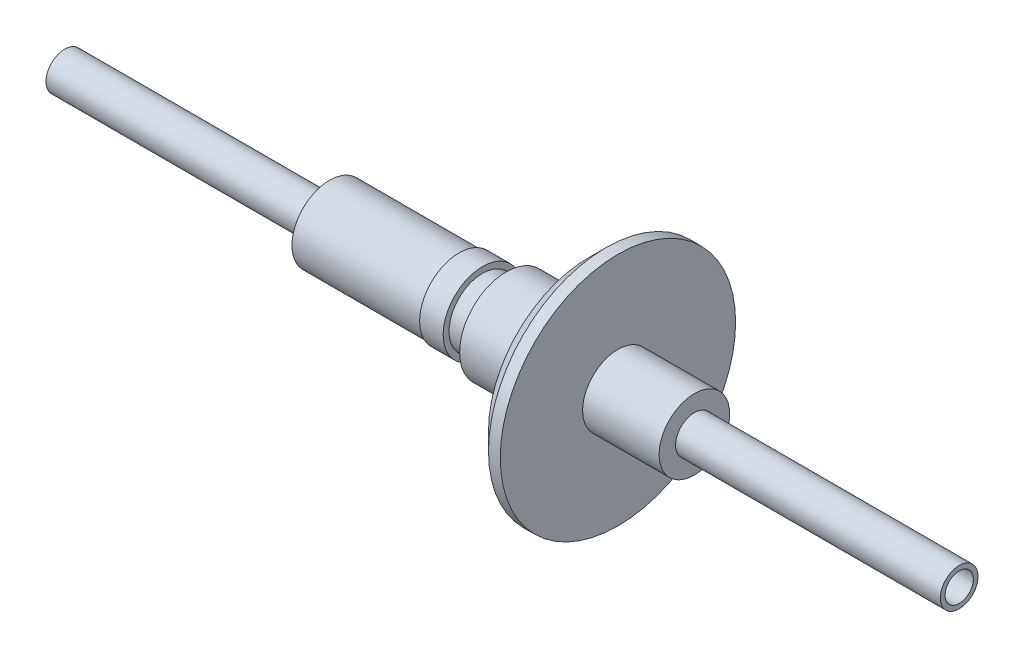
SolidWorks part; units mm, degrees
ref_plane "Front Plane" through (0, 0, 0) normal (0, 0, 1) x (1, 0, 0)
ref_plane "Top Plane" through (0, 0, 0) normal (0, 1, 0) x (1, 0, 0)
ref_plane "Right Plane" through (0, 0, 0) normal (1, 0, 0) x (0, 0, -1)
sketch "Axial profile (mm)" plane through (0, 0, 0) normal (0, 0, 1) x (1, 0, 0)
  line L0 (-110, 0) -> (75, 0) construction
  line L1 (-94, 2.4) -> (58, 2.4)
  line L2 (58, 2.4) -> (58, 3.2)
  line L3 (58, 3.2) -> (13, 3.2)
  line L4 (13, 3.2) -> (13, 6)
  line L5 (13, 6) -> (0, 6)
  line L6 (0, 6) -> (0, 20)
  line L7 (0, 20) -> (-2, 20)
  line L8 (-2, 20) -> (-5, 17)
  line L9 (-5, 17) -> (-5, 7.9)
  line L10 (-5, 7.9) -> (-19, 7.9)
  line L11 (-19, 7.9) -> (-19, 5.7)
  line L12 (-19, 5.7) -> (-23, 5.7)
  line L13 (-23, 5.7) -> (-23, 6.7)
  line L14 (-23, 6.7) -> (-27, 6.7)
  line L15 (-27, 6.7) -> (-27, 6.4)
  line L16 (-27, 6.4) -> (-49, 6.4)
  line L17 (-49, 6.4) -> (-49, 3.2)
  line L18 (-49, 3.2) -> (-94, 3.2)
  line L19 (-94, 3.2) -> (-94, 2.4)
revolve "Full revolution" add sketch "Axial profile (mm)" angle 360 about L0
